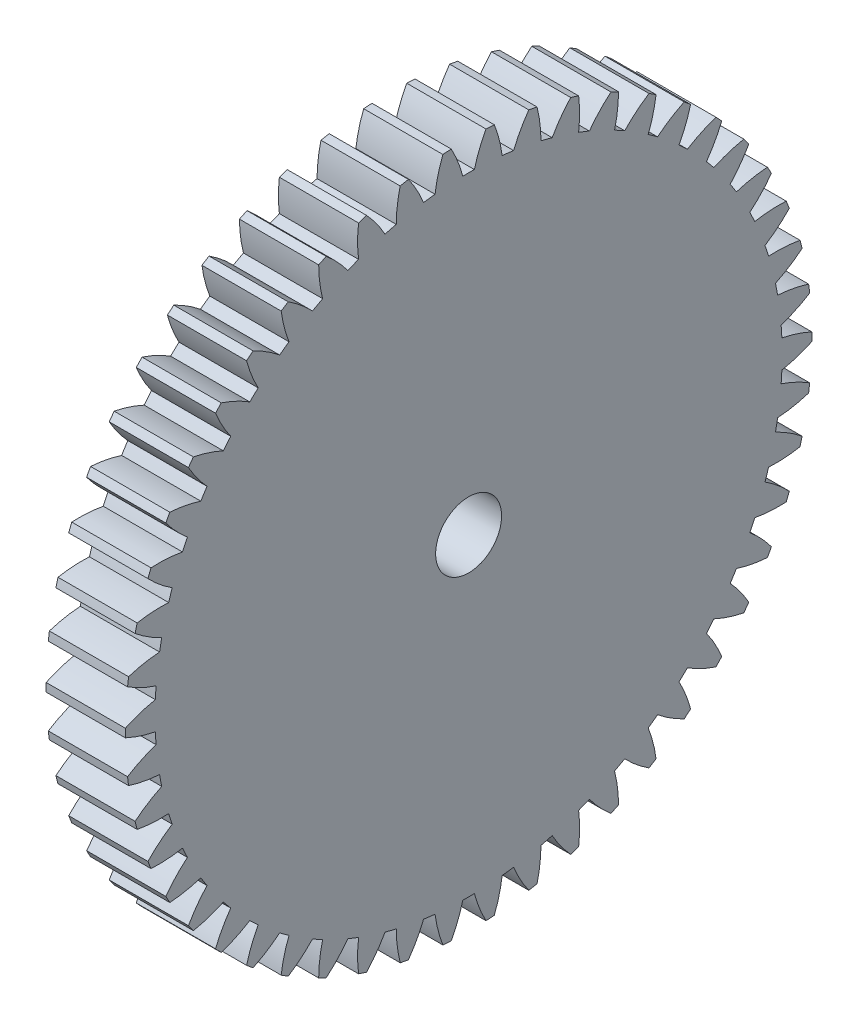
SolidWorks part; units mm, degrees
ref_plane "Plane1" through (0, 0, 0) normal (0, 0, 1) x (1, 0, 0)
ref_plane "Plane2" through (0, 0, 0) normal (0, 1, 0) x (1, 0, 0)
ref_plane "Plane3" through (0, 0, 0) normal (1, 0, 0) x (0, 0, -1)
sketch "HoldingSke" plane through (0, 0, 0) normal (0, 1, 0) x (1, 0, 0)
  line L0 (0, 0) -> (0.6428, -0.766)
  line L1 (-15, 0) -> (100, 0) construction
  line L2 (0, 0) -> (-2.1039, 2.3779)
  line L3 (0, 0) -> (-11.863, 4.5341)
  line L4 (0, 0) -> (5.5511, 6.6156)
  line L5 (0, 0) -> (-46.8476, -17.4728)
  line L6 (0, 0) -> (-3.3159, -2.2372)
  line L7 (-2.1039, 2.3779) -> (8.6586, 51.2059)
  line L8 (-76.2, 54.61) -> (-75.3, 54.61)
  line L9 (-71.009, 38.7566) -> (-53.1078, 45.2721)
  line L10 (-76.2, 71.12) -> (104.1128, 71.12)
  line L11 (0, 0) -> (-4, 0)
  line L12 (-76.2, 101.6) -> (-76.162, 101.6)
  line L13 (24.9733, 27.94) -> (52.9518, 28.4284)
  line L14 (24.9733, 27.94) -> (24.9743, 27.94)
  line L15 (24.9733, 27.94) -> (100.4006, 29.5858)
  line L16 (-63.627, -1) -> (-12.827, -1)
  circle A0 centre (0, 0) radius 2.5
  circle A1 centre (0, 0) radius 23.749
  circle A2 centre (0, 0) radius 37.5
  circle A3 centre (0, 0) radius 2.5
  dimension "MHD" = 47.498
  dimension "Hub_dia" = 75
  dimension "Bore" = 5
  dimension "MBD" = 5
  dimension "Num_teeth" = 50
  dimension "Pitch_radius" = 180.3128
  dimension "Pitch" = 1
  dimension "Width" = 4
  dimension "Overall_len" = 50
  dimension "Show_teeth" = 50
  dimension "Thickness" = 4
  dimension "OAL" = 50.0001
  dimension "T_dim" = 0.9
  dimension "Ap" = 20
  dimension "H" = 19.05
  dimension "Backlash" = 0.038
  dimension "Addendum_fac" = 1
  dimension "Dedendum_fac" = 1.25
  dimension "Clearance_fac" = 0.25
  dimension "Dedendum_add" = 0.001
  dimension "Module" = 1
sketch "BasProSke" plane through (0, 0, 0) normal (0, 1, 0) x (1, 0, 0)
  line L0 (-10, 0) -> (60, 0) construction
  line L1 (0, 0) -> (0, 26)
  line L2 (0, 0) -> (6, 0)
  line L3 (6, 0) -> (6, 26)
  line L4 (6, 26) -> (0, 26)
  dimension "Diameter" = 52
  dimension "Thickness" = 6
revolve "Base-Revolve" add sketch "BasProSke" angle 360 about L0
sketch "TooCutSke" plane through (0, 0, 0) normal (1, 0, 0) x (0, 0, -1)
  line L1 (0, 0) -> (0, 107) construction
  line L2 (0, 0) -> (-0.8518, 24.9855) construction
  line L3 (0, 0) -> (-3.1382, 49.8807) construction
  line L4 (-0.8518, 24.9855) -> (-1.5691, 24.9404) construction
  arc A0 (0.4377, 23.745) -> (-0.4377, 23.745) centre (0, 0) ccw
  arc A1 (1.3294, 25.9914) -> (-1.3294, 25.9914) centre (0, 0) ccw
  circle A2 centre (0, 0) radius 25 construction
  circle A3 centre (0, 0) radius 23.4923 construction
  arc A4 (-0.4377, 23.745) -> (-1.3294, 25.9914) centre (-10.1099, 21.2056) ccw
  arc A5 (1.3294, 25.9914) -> (0.4377, 23.745) centre (10.1099, 21.2056) ccw
  dimension "Root_dia" = 47.498
  dimension "Overcut_dia" = 52.0508
  dimension "Pitch_dia" = 50
  dimension "Base_dia" = 46.9846
  dimension "Flank_rad" = 10
  dimension "Half_ang" = 3.6
  dimension "Half_CT" = 0.7188
extrude "ToothCut" cut sketch "TooCutSke" along normal through all
fillet "Breaks" [suppressed] radius 0.02
fillet "RootFillets" [suppressed] radius 0.251
pattern_circular "TeethCuts" count 50 every 7.2 about axis through (-10, 0, 0) along (1, 0, 0) of "ToothCut", "RootFillets", "Breaks"
sketch "HubNeaOneSke" plane through (0, 0, 0) normal (-1, 0, 0) x (0, 0, 1)
  circle A0 centre (0, 0) radius 23.749
  dimension "Diameter" = 47.498
extrude "HubNearOne" [suppressed] add sketch "HubNeaOneSke" along normal blind 44.0001
sketch "HubNeaBotSke" plane through (0, 0, 0) normal (-1, 0, 0) x (0, 0, 1)
  circle A0 centre (0, 0) radius 23.749
  dimension "Diameter" = 47.498
extrude "HubNearBoth" [suppressed] add sketch "HubNeaBotSke" along normal blind 22
ref_plane "FarPln" through (6, 0, 0) normal (1, 0, 0) x (0, 0, -1)
sketch "HubFarSke" plane through (6, 0, 0) normal (1, 0, 0) x (0, 0, -1)
  circle A0 centre (0, 0) radius 23.749
  dimension "Diameter" = 47.498
extrude "HubFar" [suppressed] add sketch "HubFarSke" along normal blind 22
sketch "BorSke" plane through (0, 0, 0) normal (1, 0, 0) x (0, 0, -1)
  circle A0 centre (0, 0) radius 2.5
  dimension "Diameter" = 5
extrude "Bore" cut sketch "BorSke" along normal mid plane 100.0001
sketch "KeySke" plane through (0, 0, 0) normal (1, 0, 0) x (0, 0, -1)
  line L0 (-1, 0) -> (-1, 3.4)
  line L1 (-1, 3.4) -> (1, 3.4)
  line L2 (1, 3.4) -> (1, 0)
  line L3 (0, 0) -> (0, 34) construction
  line L4 (-1, 0) -> (1, 0)
  dimension "Offset" = 3.4
  dimension "Width" = 2
extrude "Keyway" [suppressed] cut sketch "KeySke" along normal mid plane 100.0001
pattern_circular "Keyway2" [suppressed] count 2 every 90 about axis through (-10, 0, 0) along (1, 0, 0)
hole_wizard "Ø2.05 (2.05) Diameter Hole1" [suppressed] positions "Sketch1" profile "Sketch2" hole size "Ø2.05" standard "ISO"
sketch "Sketch1" plane through (-8.7955, -164.7867, -27.9652) normal (-1, 0, 0) x (0, 0, 1)
  circle A0 centre (27.9652, 165.9867) radius 4.5
  point P0 (32.4472, 165.5842)
  point P2 (25.3756, 162.3065)
  point P4 (26.0728, 170.0695)
sketch "Sketch2" plane through (-8.7955, 0.7975, 4.482) normal (0, 1, 0) x (0, 0, 1)
  line L0 (0, 0) -> (0, 14.7955)
  line L1 (0, 14.7955) -> (1.025, 14.7955)
  line L2 (1.025, 14.7955) -> (1.025, 0)
  line L3 (1.025, 0) -> (0, 0)
  line L4 (0, -6.35) -> (0, 107.95) construction
  dimension "Thru Hole Dia." = 2.05
  dimension "Thru Hole Depth" = 14.7955
extrude "Cut-Extrude1" [suppressed] cut sketch "Sketch3" against normal through all
sketch "Sketch3" plane through (97.0946, -158.9017, -50.9706) normal (0, -0.2478, 0.9688) x (1, 0, 0)
  line L0 (-97.2608, 178.6173) -> (-97.2608, 177.8807)
  line L1 (-97.2608, 178.6173) -> (-90.708, 178.6173)
  line L2 (-97.2608, 177.8807) -> (-90.708, 177.8807)
  line L3 (-90.708, 178.6173) -> (-90.708, 177.8807)
extrude "Cut-Extrude2" [suppressed] cut sketch "Sketch4" against normal through all
sketch "Sketch4" plane through (98.1535, -143.1711, 39.9953) normal (0, 0.3332, 0.9428) x (1, 0, 0)
  line L0 (-90.708, 159.0525) -> (-90.708, 158.3159)
  line L1 (-90.708, 159.0525) -> (-100.4914, 159.0525)
  line L2 (-90.708, 158.3159) -> (-100.4914, 158.3159)
  line L3 (-100.4914, 159.0525) -> (-100.4914, 158.3159)
hole_wizard "Ø2.05 (2.05) Diameter Hole2" [suppressed] positions "Sketch5" profile "Sketch6" hole size "Ø2.05" standard "ISO"
sketch "Sketch5" plane through (-6.7366, -113.3137, 124.4735) normal (-1, 0, 0) x (0, 0.841, 0.541)
  circle A0 centre (27.9652, 165.9867) radius 4.5
  point P0 (32.4472, 165.5842)
  point P2 (25.3756, 162.3065)
  point P4 (26.0728, 170.0695)
sketch "Sketch6" plane through (-6.7366, 3.5518, 2.7631) normal (0, 1, 0) x (0, 0, 1)
  line L0 (0, 0) -> (0, 12.7366)
  line L1 (0, 12.7366) -> (1.025, 12.7366)
  line L2 (1.025, 12.7366) -> (1.025, 0)
  line L3 (1.025, 0) -> (0, 0)
  line L4 (0, -6.35) -> (0, 107.95) construction
  dimension "Thru Hole Dia." = 2.05
  dimension "Thru Hole Depth" = 12.7366
equation "' \"Module@HoldingSke\" = 6.35"
equation "' \"Num_teeth@HoldingSke\" = 12"
equation "' \"Ap@HoldingSke\" =  20"
equation "' \"Width@HoldingSke\" = 0.5 * 25.4"
equation "' \"Hub_dia@HoldingSke\"= 1 * 25.4"
equation "' \"Overall_len@HoldingSke\" = 1.0 * 25.4"
equation "' \"Bore@HoldingSke\" = 0.75 * 25.4"
equation "' \"T_dim@HoldingSke\" = 0.1 * 25.4"
equation "' \"Width@KeySke\" = 0.25 * 25.4"
equation "' \"Show_teeth@HoldingSke\" = 13"
equation "' \"Backlash@HoldingSke\" = 0.009 * 25.4"
equation "' \"Addendum_fac@HoldingSke\" = 1.0"
equation "' \"Dedendum_fac@HoldingSke\" = 1.25"
equation "' \"Dedendum_add@HoldingSke\" = 0.00005 * 25.4"
equation "' \"Clearance_fac@HoldingSke\" = 0.25"
equation "\"Pitch@HoldingSke\" = 1 / \"Module@HoldingSke\""
equation "\"Overcut_dia@TooCutSke\" = (\"Num_teeth@HoldingSke\" + 2 * \"Addendum_fac@HoldingSke\") / \"Pitch@HoldingSke\" + 0.002 * 25.4"
equation "\"Pitch_dia@TooCutSke\" = \"Num_teeth@HoldingSke\" / \"Pitch@HoldingSke\""
equation "\"Base_dia@TooCutSke\" = \"Num_teeth@HoldingSke\" / \"Pitch@HoldingSke\" * cos((\"Ap@HoldingSke\"  * 3.14159265 / 180))"
equation "\"Root_dia@TooCutSke\" = (\"Num_teeth@HoldingSke\" + 2) / \"Pitch@HoldingSke\" - 2 * (\"Addendum_fac@HoldingSke\" + \"Dedendum_fac@HoldingSke\") / \"Pitch@HoldingSke\" - \"Dedendum_add@HoldingSke\" * 2"
equation "\"Half_ang@TooCutSke\" = 180 / \"Num_teeth@HoldingSke\""
equation "\"Half_CT@TooCutSke\" = \"Num_teeth@HoldingSke\" / \"Pitch@HoldingSke\" * sin((3.14159265 / 2 / \"Num_teeth@HoldingSke\")) / 2 - 7 * \"Backlash@HoldingSke\" / 4"
equation "\"Flank_rad@TooCutSke\" = \"Num_teeth@HoldingSke\" / \"Pitch@HoldingSke\" / 5"
equation "\"Radius@RootFillets\" = \"Clearance_fac@HoldingSke\" / \"Pitch@HoldingSke\" + \"Dedendum_add@HoldingSke\""
equation "\"Break_rad@Breaks\" = 0.02 / \"Pitch@HoldingSke\""
equation "\"Thickness@HoldingSke\" = \"Width@HoldingSke\""
equation "\"OAL@HoldingSke\" = \"Thickness@HoldingSke\""
equation "\"MHD@HoldingSke\" = (\"Num_teeth@HoldingSke\" + 2) / \"Pitch@HoldingSke\" - 2 * (\"Addendum_fac@HoldingSke\" + \"Dedendum_fac@HoldingSke\")  / \"Pitch@HoldingSke\" - \"Dedendum_add@HoldingSke\" * 2"
equation "\"MBD@HoldingSke\" = (\"Num_teeth@HoldingSke\" + 2) / \"Pitch@HoldingSke\" - 2 * (\"Addendum_fac@HoldingSke\" + \"Dedendum_fac@HoldingSke\")  / \"Pitch@HoldingSke\" - \"Dedendum_add@HoldingSke\" * 2 - 0.002 * 25.4"
equation "\"MHD@HoldingSke\" = ((sgn( \"MHD@HoldingSke\" - \"Hub_dia@HoldingSke\" )-1)*( \"MHD@HoldingSke\" - \"Hub_dia@HoldingSke\" ))/-2+ \"Hub_dia@HoldingSke\""
equation "\"MBD@HoldingSke\" = ((sgn( \"MBD@HoldingSke\" - \"Bore@HoldingSke\" )-1)*( \"MBD@HoldingSke\" - \"Bore@HoldingSke\" ))/-2+ \"Bore@HoldingSke\""
equation "\"OAL@HoldingSke\" = ((sgn( \"OAL@HoldingSke\" - \"Overall_len@HoldingSke\" )+1)*( \"OAL@HoldingSke\" - \"Overall_len@HoldingSke\" ))/2 + \"Overall_len@HoldingSke\" + 0.000002 * 25.4"
equation "\"Num_teeth@TeethCuts\" = int( \"Show_teeth@HoldingSke\" ) + 1"
equation "\"Num_teeth@TeethCuts\" = ((sgn( \"Num_teeth@TeethCuts\" - \"Num_teeth@HoldingSke\" )-1)*( \"Num_teeth@TeethCuts\" - \"Num_teeth@HoldingSke\" ))/-2+ \"Num_teeth@HoldingSke\""
equation "\"Num_teeth@TeethCuts\" = ((sgn( \"Num_teeth@TeethCuts\" - 2.0)+1)*( \"Num_teeth@TeethCuts\" - 2.0))/2 +2.0"
equation "\"Angle@TeethCuts\" = 360.0 / \"Num_teeth@HoldingSke\""
equation "\"Diameter@BasProSke\" = (\"Num_teeth@HoldingSke\" + 2 * \"Addendum_fac@HoldingSke\") / \"Pitch@HoldingSke\""
equation "' \"Fillet_rad@BasProSke\" =  \"Thickness@HoldingSke\" * 0.05"
equation "\"MHD@HoldingSke\" = ((sgn( \"MHD@HoldingSke\" - \"Root_dia@TooCutSke\" )-1)*( \"MHD@HoldingSke\" - \"Root_dia@TooCutSke\" ))/-2+ \"Root_dia@TooCutSke\""
equation "\"Diameter@HubNeaOneSke\" = \"MHD@HoldingSke\""
equation "\"Length@HubNearOne\" = \"OAL@HoldingSke\" - \"Thickness@BasProSke\""
equation "\"Diameter@HubNeaBotSke\" = \"MHD@HoldingSke\""
equation "\"Length@HubNearBoth\" = ( \"OAL@HoldingSke\" - \"Thickness@BasProSke\" ) / 2.0"
equation "\"Thickness@FarPln\" = \"Thickness@BasProSke\""
equation "\"Diameter@HubFarSke\" = \"MHD@HoldingSke\""
equation "\"Length@HubFar\" = ( \"OAL@HoldingSke\" - \"Thickness@BasProSke\" ) / 2.0"
equation "\"Diameter@BorSke\" = \"MBD@HoldingSke\""
equation "\"D1@Bore\" = \"OAL@HoldingSke\" * 2.0"
equation "\"D1@Keyway\" = \"OAL@HoldingSke\" * 2.0"
equation "\"Offset@KeySke\" = \"T_dim@HoldingSke\" + \"MBD@HoldingSke\" / 2.0"
